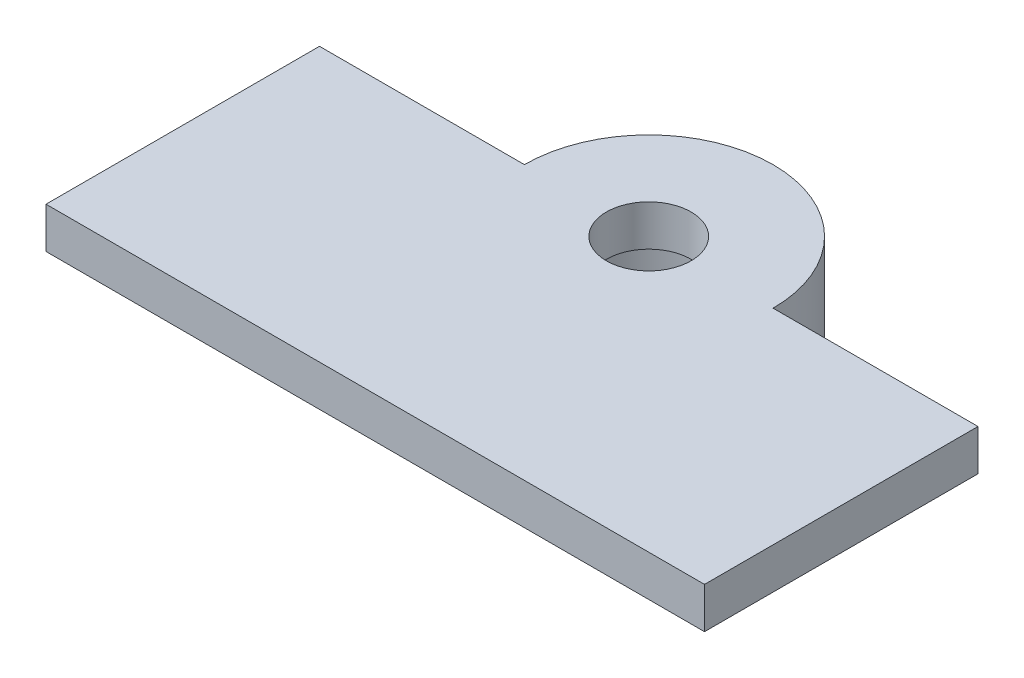
SolidWorks part; units mm, degrees
ref_plane "Front Plane" through (0, 0, 0) normal (0, 0, 1) x (1, 0, 0)
ref_plane "Top Plane" through (0, 0, 0) normal (0, 1, 0) x (1, 0, 0)
ref_plane "Right Plane" through (0, 0, 0) normal (1, 0, 0) x (0, 0, -1)
sketch "Sketch1" plane through (0, 0, 0) normal (0, 1, 0) x (1, 0, 0)
  circle A0 centre (0, 0) radius 6.1
  circle A1 centre (0, 0) radius 9.1
  dimension "D1" = 12.2
  dimension "D2" = 3
extrude "Boss-Extrude1" add sketch "Sketch1" along normal blind 10
sketch "Sketch2" plane through (0, 10, 0) normal (0, 1, 0) x (1, 0, 0)
  circle A0 centre (0, 0) radius 9.1 construction
  circle A1 centre (0, 0) radius 9.1
  circle A2 centre (0, 0) radius 3.1
  dimension "D1" = 6.2
extrude "Boss-Extrude2" add sketch "Sketch2" along normal blind 3
sketch "Sketch3" plane through (0, 13, 0) normal (0, 1, 0) x (1, 0, 0)
  line L0 (-9.1, 0) -> (-24.1, 0)
  line L1 (-24.1, 0) -> (-24.1, -20.0185)
  line L2 (-24.1, -20.0185) -> (24.1, -20.0185)
  line L3 (24.1, -20.0185) -> (24.1, 0)
  line L4 (24.1, 0) -> (9.1, 0)
  line L5 (9.1, 0) -> (0, -6.0297)
  line L6 (0, -6.0297) -> (-9.1, 0)
  circle A0 centre (0, 0) radius 9.1 construction
  dimension "D1" = 15
extrude "Boss-Extrude3" add sketch "Sketch3" against normal blind 3
